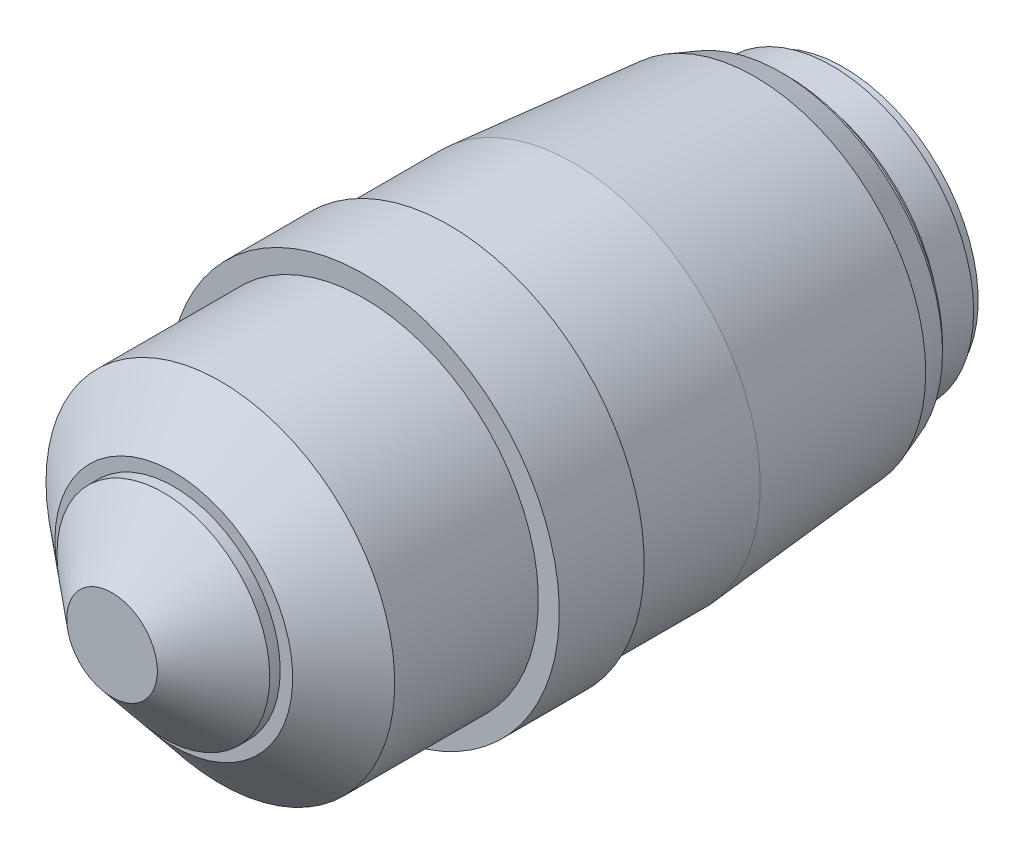
SolidWorks part; units mm, degrees
ref_plane "Front Plane" through (0, 0, 0) normal (0, 0, 1) x (1, 0, 0)
ref_plane "Top Plane" through (0, 0, 0) normal (0, 1, 0) x (1, 0, 0)
ref_plane "Right Plane" through (0, 0, 0) normal (1, 0, 0) x (0, 0, -1)
sketch "Sketch1" plane through (0, 0, 0) normal (0, 1, 0) x (1, 0, 0)
  line L0 (0, 0) -> (0, 64.98) construction
  line L1 (0, 0.38) -> (4, 0.38)
  line L2 (0, 0) -> (4, 0) construction
  line L3 (0, 0.17) -> (4, 0.17) construction
  line L4 (4, 0.38) -> (9.4, 4.9111)
  line L5 (9.4, 4.9111) -> (9.4, 5.8341)
  line L6 (9.4, 5.8341) -> (10.5, 5.8341)
  line L7 (10.5, 5.8341) -> (15.4, 9.9457)
  line L8 (15.4, 9.9457) -> (15.4, 22.6341)
  line L9 (15.4, 22.6341) -> (17.25, 22.6341)
  line L10 (17.25, 22.6341) -> (17.25, 30.1341)
  line L11 (17.25, 30.1341) -> (16.5, 30.1341)
  line L12 (16.5, 30.1341) -> (16.5, 41.1341)
  line L13 (16.5, 41.1341) -> (15.099, 57.1473)
  line L14 (15.099, 57.1473) -> (14.25, 59.48)
  line L15 (14.25, 59.48) -> (13.75, 59.48)
  line L16 (13.75, 59.48) -> (13.75, 59.98)
  line L17 (13.75, 59.98) -> (11.9, 59.98)
  line L18 (11.9, 59.98) -> (11.9, 60.98)
  line L19 (11.9, 60.98) -> (12.5, 60.98)
  line L20 (12.5, 60.98) -> (12.5, 63.98)
  line L21 (12.5, 63.98) -> (11.9, 63.98)
  line L22 (11.9, 63.98) -> (11.9, 64.98)
  line L23 (11.9, 64.98) -> (0, 64.98)
  line L24 (0, 64.98) -> (0, 0.38)
  point P15 (9.95, 5.8341)
  point P36 (12.825, 59.98)
  dimension "D2" = 4
  dimension "D3" = 0.17
  dimension "D4" = 0.21
  dimension "D5" = 40
  dimension "D6" = 9.4
  dimension "D7" = 10.5
  dimension "D8" = 16.8
  dimension "D9" = 15.4
  dimension "D10" = 17.25
  dimension "D11" = 7.5
  dimension "D12" = 16.5
  dimension "D13" = 5
  dimension "D14" = 11
  dimension "D15" = 59.6
  dimension "D16" = 14.25
  dimension "D17" = 5
  dimension "D18" = 70
  dimension "D19" = 1
  dimension "D20" = 11.9
  dimension "D21" = 1
  dimension "D22" = 12.5
  dimension "D23" = 0.5
  dimension "D24" = 0.5
revolve "Revolve1" add sketch "Sketch1" angle 360 about L24
ref_plane "IP" through (0, 0, 0.08) normal (0, 0, -1) x (-1, 0, 0)
sketch "Sketch2" plane through (0, 0, -64.98) normal (0, 0, -1) x (-1, 0, 0)
  circle A0 centre (0, 0) radius 4.75
  dimension "D1" = 9.5
extrude "Cut-Extrude1" cut sketch "Sketch2" against normal blind 1
